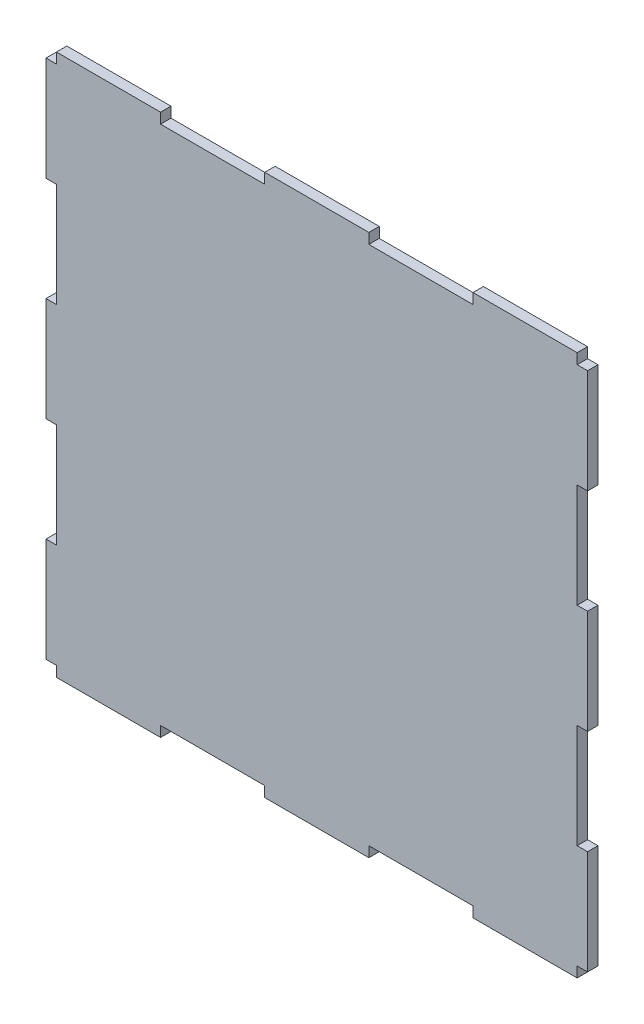
SolidWorks part; units mm, degrees
material "Pinho"
ref_plane "Plano frontal" through (0, 0, 0) normal (0, 0, 1) x (1, 0, 0)
ref_plane "Plano superior" through (0, 0, 0) normal (0, 1, 0) x (1, 0, 0)
ref_plane "Plano direito" through (0, 0, 0) normal (1, 0, 0) x (0, 0, -1)
sketch "Esboço1" plane through (0, 0, 0) normal (0, 0, 1) x (1, 0, 0)
  line L0 (-82.2996, -120) -> (-82.2996, -90)
  line L1 (40.7004, -120) -> (10.7004, -120)
  line L3 (40.7004, 30) -> (10.7004, 30)
  line L6 (-19.2996, 30) -> (-49.2996, 30)
  line L7 (-79.2996, 30) -> (-82.2996, 30)
  line L11 (-79.2996, -120) -> (-82.2996, -120)
  line L15 (-82.2996, -90) -> (-79.2996, -90)
  line L25 (-79.2996, 30) -> (-79.2996, 33)
  line L26 (70.7004, 30) -> (73.7004, 30)
  line L34 (-79.2996, 33) -> (-49.2996, 33)
  line L35 (-49.2996, 30) -> (-49.2996, 33)
  line L37 (70.7004, 30) -> (70.7004, 33)
  line L38 (70.7004, 33) -> (40.7004, 33)
  line L39 (40.7004, 30) -> (40.7004, 33)
  line L41 (-19.2996, 30) -> (-19.2996, 33)
  line L42 (-19.2996, 33) -> (10.7004, 33)
  line L43 (10.7004, 30) -> (10.7004, 33)
  line L44 (-19.2996, -120) -> (-49.2996, -120)
  line L46 (-19.2996, -120) -> (-19.2996, -123)
  line L47 (-19.2996, -123) -> (10.7004, -123)
  line L48 (10.7004, -120) -> (10.7004, -123)
  line L49 (-79.2996, -90) -> (-79.2996, -60)
  line L50 (-79.2996, -60) -> (-82.2996, -60)
  line L52 (-79.2996, -120) -> (-79.2996, -123)
  line L53 (-79.2996, -123) -> (-49.2996, -123)
  line L54 (-49.2996, -120) -> (-49.2996, -123)
  line L57 (70.7004, -123) -> (40.7004, -123)
  line L58 (40.7004, -120) -> (40.7004, -123)
  line L59 (-82.2996, -60) -> (-82.2996, -30)
  line L60 (-82.2996, -30) -> (-79.2996, -30)
  line L62 (-82.2996, 30) -> (-82.2996, 0)
  line L63 (-82.2996, 0) -> (-79.2996, 0)
  line L64 (-79.2996, 0) -> (-79.2996, -30)
  line L65 (70.7004, -123) -> (70.7004, -120)
  line L66 (70.7004, -120) -> (73.7004, -120)
  line L67 (73.7004, -120) -> (73.7004, -90)
  line L68 (73.7004, -90) -> (70.7004, -90)
  line L69 (70.7004, -90) -> (70.7004, -60)
  line L70 (70.7004, -60) -> (73.7004, -60)
  line L71 (73.7004, -60) -> (73.7004, -30)
  line L72 (73.7004, -30) -> (70.7004, -30)
  line L73 (70.7004, -30) -> (70.7004, 0)
  line L74 (70.7004, 0) -> (73.7004, 0)
  line L75 (73.7004, 0) -> (73.7004, 30)
  point P0 (0, 0)
  dimension "D1" = 150
  dimension "D2" = 150
  dimension "D3" = 3
  dimension "D4" = 30
  dimension "D5" = 30
  dimension "D6" = 30
  dimension "D7" = 30
  dimension "D8" = 30
  dimension "D9" = 30
  dimension "D10" = 30
  dimension "D16" = 30
  dimension "D17" = 30
  dimension "D18" = 30
  dimension "D19" = 3
  dimension "D20" = 3
  dimension "D21" = 3
  dimension "D22" = 30
  dimension "D23" = 30
  dimension "D24" = 30
  dimension "D25" = 3
  dimension "D26" = 3
  dimension "D27" = 3
extrude "Ressalto-extrusão1" add sketch "Esboço1" along normal blind 3
